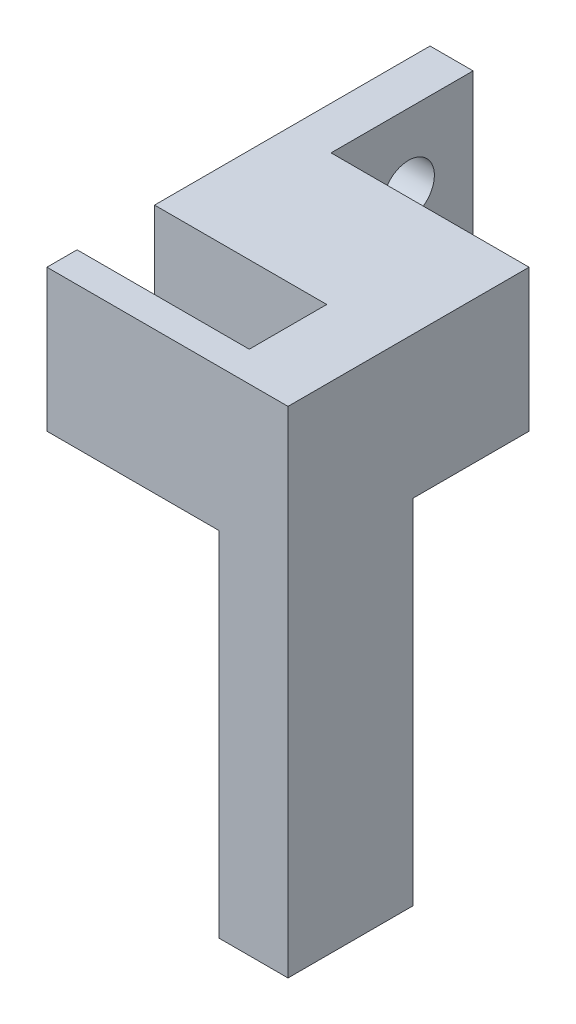
SolidWorks part; units mm, degrees
ref_plane "前视基准面" through (0, 0, 0) normal (0, 0, 1) x (1, 0, 0)
ref_plane "上视基准面" through (0, 0, 0) normal (0, 1, 0) x (1, 0, 0)
ref_plane "右视基准面" through (0, 0, 0) normal (1, 0, 0) x (0, 0, -1)
other "Configuration Table"
sketch "草图1" plane through (0, 0, 0) normal (1, 0, 0) x (0, 0, -1)
  line L5 (0, 0) -> (-2.9, 0)
  line L6 (0, 0) -> (0, -11.5)
  line L7 (0, -11.5) -> (-2.9, -11.5)
  line L8 (-2.9, 0) -> (-2.9, -11.5)
  dimension "D1" = 2.9
  dimension "D2" = 11.5
extrude "凸台-拉伸1" add sketch "草图1" along normal blind 1.6
sketch "草图2" plane through (0, 0, 0) normal (-1, 0, 0) x (0, 0, 1)
  line L0 (2.9, 0) -> (2.9, -11.5) construction
  line L1 (2.2, -3.3) -> (2.9, -3.3)
  line L2 (2.2, -3.3) -> (2.2, 0)
  line L3 (2.2, 0) -> (2.9, 0)
  line L4 (2.9, -3.3) -> (2.9, 0)
  line L5 (0, 0) -> (2.9, 0) construction
  line L6 (0, 0) -> (0.4, 0)
  line L7 (0, 0) -> (0, -3.3)
  line L8 (0, -3.3) -> (0.4, -3.3)
  line L9 (0.4, 0) -> (0.4, -3.3)
  dimension "D1" = 3.3
  dimension "D2" = 0.7
  dimension "D3" = 0.4
extrude "凸台-拉伸2" add sketch "草图2" along normal blind 4 contours L4 L3 L2 L1 | L9 L8 L7 L6
sketch "草图3" plane through (0, 0, 0) normal (0, 0, -1) x (-1, 0, 0)
  line L0 (-1.6, 0) -> (4, 0) construction
  line L1 (-1.6, 0) -> (4, 0)
  line L2 (-1.6, 0) -> (-1.6, -3.3)
  line L3 (-1.6, -3.3) -> (4, -3.3)
  line L4 (4, 0) -> (4, -3.3)
  line L5 (4, 0) -> (4, -3.3) construction
  line L6 (-1.6, 0) -> (-1.6, -11.5) construction
  line L7 (4, -3.3) -> (0, -3.3) construction
extrude "凸台-拉伸3" add sketch "草图3" along normal blind 3
sketch "草图4" plane through (0, 0, -3) normal (0, 0, -1) x (-1, 0, 0)
  line L0 (-1.6, -3.3) -> (4, -3.3) construction
  line L1 (3, -3.3) -> (4, -3.3)
  line L2 (3, -3.3) -> (3, 0)
  line L3 (3, 0) -> (4, 0)
  line L4 (4, -3.3) -> (4, 0)
  line L5 (4, -3.3) -> (4, 0) construction
  line L6 (4, 0) -> (-1.6, 0) construction
  dimension "D1" = 1
extrude "凸台-拉伸4" add sketch "草图4" along normal blind 3
sketch "草图5" plane through (-3, 0, 0) normal (1, 0, 0) x (0, 0, -1)
  line L1 (4.5, 0) -> (4.5, -3.3)
  line L2 (6, 0) -> (3, 0) construction
  line L3 (6, -3.3) -> (3, -3.3) construction
  circle A0 centre (4.5, -1.65) radius 0.6
  dimension "D1" = 1.2
extrude "切除-拉伸1" cut sketch "草图5" against normal through all contours A0
sketch "草图6" plane through (0, 0, -3) normal (0, 0, -1) x (-1, 0, 0)
  line L0 (-1.6, -3.3) -> (3, -3.3) construction
  line L1 (-1.6, -3.3) -> (3, -3.3)
  line L2 (-1.6, -3.3) -> (-1.6, 0)
  line L3 (-1.6, 0) -> (3, 0)
  line L4 (3, -3.3) -> (3, 0)
  line L5 (-1.6, -3.3) -> (-1.6, -11.5) construction
  line L6 (3, 0) -> (3, -3.3) construction
  line L7 (3, 0) -> (-1.6, 0) construction
extrude "切除-拉伸2" cut sketch "草图6" against normal blind 0.3
